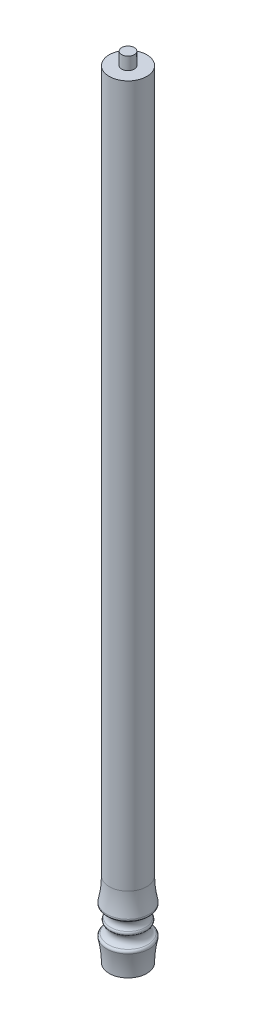
SolidWorks part; units mm, degrees
ref_plane "Front Plane" through (0, 0, 0) normal (0, 0, 1) x (1, 0, 0)
ref_plane "Top Plane" through (0, 0, 0) normal (0, 1, 0) x (1, 0, 0)
ref_plane "Right Plane" through (0, 0, 0) normal (1, 0, 0) x (0, 0, -1)
ref_plane "Plane3" through (0, 787.4, 0) normal (0, 1, 0) x (1, 0, 0)
ref_plane "Plane4" through (0, 800.1, 0) normal (0, 1, 0) x (1, 0, 0)
ref_plane "Plane5" through (0, 165.1, 0) normal (0, 1, 0) x (1, 0, 0)
ref_plane "Plane6" through (0, 203.2, 0) normal (0, 1, 0) x (1, 0, 0)
ref_plane "Plane7" through (0, 254, 0) normal (0, 1, 0) x (1, 0, 0)
ref_plane "Plane8" through (0, 25.4, 0) normal (0, 1, 0) x (1, 0, 0)
ref_plane "Plane9" through (0, 38.1, 0) normal (0, 1, 0) x (1, 0, 0)
ref_plane "Plane10" through (0, 50.8, 0) normal (0, 1, 0) x (1, 0, 0)
ref_plane "Plane11" through (0, 76.2, 0) normal (0, 1, 0) x (1, 0, 0)
ref_plane "Plane14" through (6.35, 0, 0) normal (1, 0, 0) x (0, 0, -1)
ref_plane "Plane15" through (15.875, 0, 0) normal (1, 0, 0) x (0, 0, -1)
ref_plane "Plane16" through (19.05, 0, 0) normal (1, 0, 0) x (0, 0, -1)
ref_plane "Plane17" through (22.225, 0, 0) normal (1, 0, 0) x (0, 0, -1)
sketch "center" plane through (0, 0, 0) normal (0, 0, 1) x (1, 0, 0)
  line L0 (0, 0) -> (0, 787.4)
  line L7 (154.1749, 787.4) -> (-154.1749, 787.4) construction
  line L13 (0, -76.5499) -> (0, 76.5499) construction
  point P5 (0, 0)
  point P6 (0, 0)
ref_axis "Axis1" through (0, -55, 0) along (0, 1, 0)
sketch "Sketch5" plane through (0, 25.4, 0) normal (0, 1, 0) x (1, 0, 0)
  line L0 (22.225, -76.5499) -> (22.225, 76.5499) construction
  circle A0 centre (0, 0) radius 22.225
ref_plane "Plane18" through (0, 31.75, 0) normal (0, 1, 0) x (1, 0, 0)
ref_plane "Plane19" through (0, 44.45, 0) normal (0, 1, 0) x (1, 0, 0)
sketch "Sketch6" plane through (0, 31.75, 0) normal (0, 1, 0) x (1, 0, 0)
  line L0 (15.875, -76.5499) -> (15.875, 76.5499) construction
  circle A0 centre (0, 0) radius 15.875
sketch "Sketch7" plane through (0, 38.1, 0) normal (0, 1, 0) x (1, 0, 0)
  circle A0 centre (0, 0) radius 18.9864
sketch "Sketch8" plane through (0, 44.45, 0) normal (0, 1, 0) x (1, 0, 0)
  circle A0 centre (0, 0) radius 15.875
sketch "Sketch9" plane through (0, 50.8, 0) normal (0, 1, 0) x (1, 0, 0)
  circle A0 centre (0, 0) radius 22.225
sketch "Sketch10" plane through (0, 76.2, 0) normal (0, 1, 0) x (1, 0, 0)
  circle A0 centre (0, 0) radius 18.9864
sketch "Sketch11" plane through (0, 0, 0) normal (0, 1, 0) x (1, 0, 0)
  circle A0 centre (0, 0) radius 18.9864
sketch "revolve sketch" plane through (0, 0, 0) normal (0, 0, 1) x (1, 0, 0)
  line L0 (0, 0) -> (19.05, 0)
  line L1 (18.9864, 0) -> (-18.9864, 0) construction
  line L2 (15.875, -76.5499) -> (15.875, 76.5499) construction
  line L3 (22.225, 25.4) -> (-22.225, 25.4) construction
  line L4 (22.225, -76.5499) -> (22.225, 76.5499) construction
  line L5 (154.1749, 25.4) -> (-154.1749, 25.4) construction
  line L6 (15.875, 31.75) -> (-15.875, 31.75) construction
  line L7 (154.1749, 31.75) -> (-154.1749, 31.75) construction
  line L8 (154.1749, 38.1) -> (-154.1749, 38.1) construction
  line L9 (15.875, 44.45) -> (-15.875, 44.45) construction
  line L10 (154.1749, 44.45) -> (-154.1749, 44.45) construction
  line L11 (22.225, 50.8) -> (-22.225, 50.8) construction
  line L12 (154.1749, 50.8) -> (-154.1749, 50.8) construction
  line L17 (19.05, -76.5499) -> (19.05, 76.5499) construction
  line L18 (154.1749, 0) -> (-154.1749, 0) construction
  line L19 (18.9864, 76.2) -> (-18.9864, 76.2) construction
  line L20 (154.1749, 76.2) -> (-154.1749, 76.2) construction
  line L21 (19.05, 76.2) -> (19.05, 787.4)
  line L22 (154.1749, 787.4) -> (-154.1749, 787.4) construction
  line L23 (19.05, 787.4) -> (6.35, 787.4)
  line L24 (6.35, -76.5499) -> (6.35, 76.5499) construction
  line L25 (6.35, 787.4) -> (6.35, 800.1)
  line L26 (152.7724, 800.1) -> (-152.7724, 800.1) construction
  line L27 (6.35, 800.1) -> (0, 800.1)
  line L28 (0, -76.5499) -> (0, 76.5499) construction
  line L29 (0, 800.1) -> (0, 0)
  arc A0 (19.05, 0) -> (21.6122, 22.8517) centre (122.2375, 0) cw
  arc A1 (15.875, 31.75) -> (20.018, 25.7959) centre (22.225, 31.75) ccw
  arc A2 (15.875, 31.75) -> (17.7809, 36.2857) centre (22.225, 31.75) cw
  arc A3 (17.7809, 39.9143) -> (15.875, 44.45) centre (22.225, 44.45) cw
  arc A4 (15.875, 44.45) -> (20.018, 50.4041) centre (22.225, 44.45) cw
  arc A5 (21.6122, 53.3483) -> (19.05, 76.2) centre (122.2375, 76.2) cw
  arc A6 (17.7809, 36.2857) -> (17.7809, 39.9143) centre (16.0033, 38.1) ccw
  arc A7 (21.6122, 22.8517) -> (20.018, 25.7959) centre (19.1352, 23.4142) ccw
  arc A8 (20.018, 50.4041) -> (21.6122, 53.3483) centre (19.1352, 52.7858) ccw
  point P49 (22.225, 38.1)
  point P52 (22.225, 25.4)
  point P55 (22.225, 50.8)
  point P60 (22.225, 25.4)
  point P62 (22.225, 50.8)
  dimension "D1" = 2.54
  dimension "D2" = 2.54
  dimension "D3" = 2.54
revolve "Revolve1" add sketch "revolve sketch" angle 360 about axis through (0, -55, 0) along (0, 1, 0)
